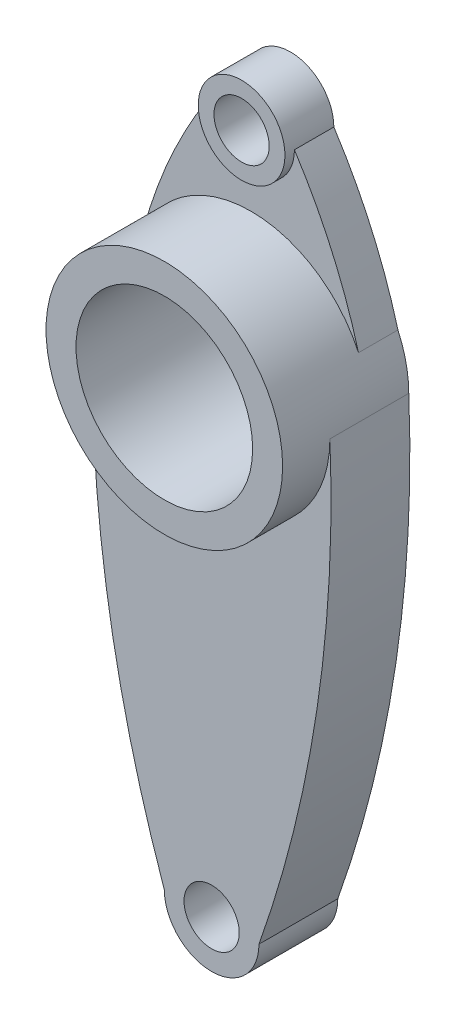
SolidWorks part; units mm, degrees
ref_plane "Front Plane" through (0, 0, 0) normal (0, 0, 1) x (1, 0, 0)
ref_plane "Top Plane" through (0, 0, 0) normal (0, 1, 0) x (1, 0, 0)
ref_plane "Right Plane" through (0, 0, 0) normal (1, 0, 0) x (0, 0, -1)
sketch "Sketch1" plane through (0, 0, 0) normal (0, 0, 1) x (1, 0, 0)
  circle A0 centre (0, 0) radius 11.2
  circle A1 centre (0, 0) radius 15
  dimension "D1" = 22.4
  dimension "D2" = 30
extrude "Boss-Extrude1" add sketch "Sketch1" along normal blind 16
sketch "Sketch2" plane through (0, 0, 0) normal (0, 0, 1) x (1, 0, 0)
  line L0 (0, 0) -> (0, 36.8124) construction
  line L1 (0, 0) -> (15, 0) construction
  line L2 (0, 0) -> (7.5, 12.9904) construction
  circle A0 centre (0, 24.5) radius 5.5
  circle A1 centre (0, 0) radius 15 construction
  circle A2 centre (0, 0) radius 15
  circle A3 centre (0, 24.5) radius 3.5
  arc A4 (-5.5, 24.5) -> (-15, 0) centre (49.1025, -10.7642) ccw
  arc A5 (5.5, 24.5) -> (15, 0) centre (-49.1025, -10.7642) cw
  circle A6 centre (-21.2176, 12.25) radius 3.5 construction
  circle A7 centre (-21.2176, 12.25) radius 5.5 construction
  arc A8 (-18.4676, 17.0131) -> (7.5, 12.9904) centre (-15.2292, -47.9061) cw construction
  arc A9 (-23.9676, 7.4869) -> (-7.5, -12.9904) centre (33.8734, 37.1419) ccw construction
  dimension "D1" = 11
  dimension "D3" = 65
  dimension "D4" = 2
  dimension "D5" = 60
  dimension "D6" = 7
  dimension "D2" = 24.5
extrude "Boss-Extrude2" add sketch "Sketch2" along normal blind 5 contours A7 A6 | A0 A5 A2 A4 | A0 A3
sketch "Sketch3" plane through (0, 0, 0) normal (0, 0, -1) x (-1, 0, 0)
  line L0 (0, 0) -> (0, -62.5919) construction
  line L1 (0, 0) -> (-15, 0)
  circle A0 centre (0, -60) radius 3.5
  circle A1 centre (0, -60) radius 6
  arc A3 (-15, 0) -> (-6, -60) centre (144.8598, -6.696) ccw
  circle A4 centre (0, 0) radius 15 construction
  arc A5 (15, 0) -> (6, -60) centre (-144.8598, -6.696) cw
  circle A6 centre (0, 0) radius 15
  dimension "D1" = 7
  dimension "D2" = 12
  dimension "D4" = 160
  dimension "D3" = 60
extrude "Boss-Extrude3" add sketch "Sketch3" against normal blind 10
sketch "Sketch4" plane through (0, 0, 5) normal (0, 0, 1) x (1, 0, 0)
  circle A1 centre (0, 24.5) radius 3.5
  circle A2 centre (0, 24.5) radius 5.5
  arc A5 (5.5, 24.5) -> (-5.5, 24.5) centre (0, 24.5) ccw construction
  dimension "D1" = 7
extrude "Boss-Extrude4" add sketch "Sketch4" along normal blind 1.2
